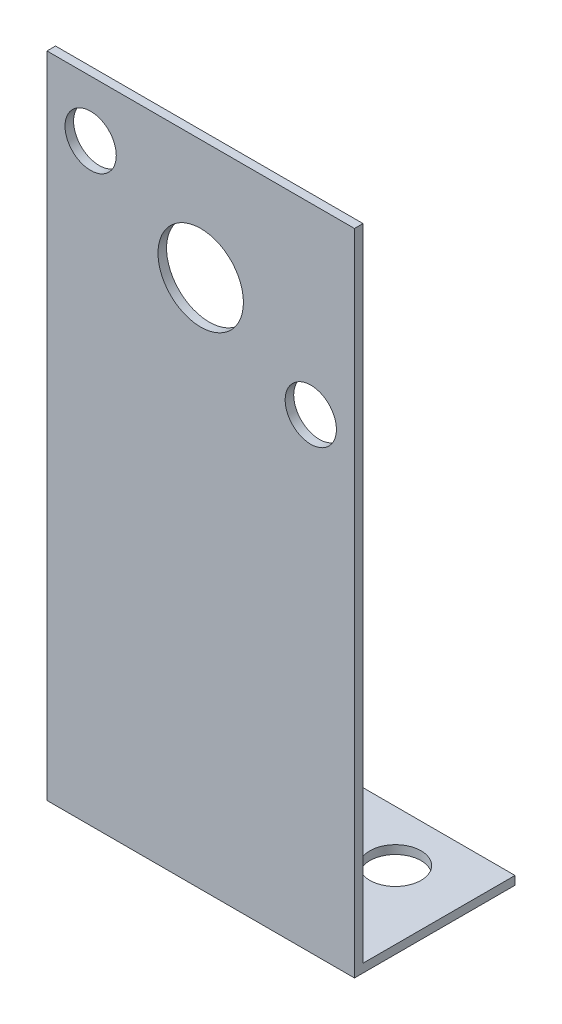
SolidWorks part; units mm, degrees
ref_plane "Front" through (0, 0, 0) normal (0, 0, 1) x (1, 0, 0)
ref_plane "Top" through (0, 0, 0) normal (0, 1, 0) x (1, 0, 0)
ref_plane "Right" through (0, 0, 0) normal (1, 0, 0) x (0, 0, -1)
sketch "Sketch1" plane through (0, 0, 0) normal (0, 0, 1) x (1, 0, 0)
  line L1 (-9, 7) -> (9, 7)
  line L2 (-9, 7) -> (-9, -31)
  line L3 (-9, -31) -> (9, -31)
  line L4 (9, 7) -> (9, -31)
  circle A0 centre (0, 0) radius 2.5
  dimension "D5" = 5
  dimension "D1" = 9
  dimension "D2" = 9
  dimension "D3" = 7
  dimension "D4" = 31
extrude "Extrude1" add sketch "Sketch1" along normal blind 0.5
sketch "Sketch2" plane through (0, 0, 0) normal (0, 0, -1) x (-1, 0, 0)
  line L0 (-9, -31) -> (-9, 7) construction
  line L1 (9, -31) -> (-9, -31)
  line L2 (9, -31) -> (9, -30.5)
  line L3 (9, -30.5) -> (-9, -30.5)
  line L4 (-9, -31) -> (-9, -30.5)
  dimension "D1" = 0.5
extrude "Extrude2" add sketch "Sketch2" along normal blind 8.9
sketch "Sketch3" plane through (0, -30.5, 0) normal (0, 1, 0) x (1, 0, 0)
  line L0 (-9, 8.9) -> (9, 8.9) construction
  line L1 (-9, 8.9) -> (-9, 0) construction
  line L2 (9, 8.9) -> (9, 0) construction
  circle A0 centre (-5, 5.9) radius 1.5
  circle A1 centre (5, 5.9) radius 1.5
  dimension "D4" = 3
  dimension "D5" = 3
  dimension "D1" = 3
  dimension "D2" = 4
  dimension "D3" = 4
extrude "Extrude3" cut sketch "Sketch3" against normal up to surface (0.5 mm away) up to face at (0, -31, -4.2)
sketch "Sketch4" plane through (0, 0, 0) normal (0, 0, -1) x (-1, 0, 0)
  circle A0 centre (-6.4432, -3.72) radius 1.5
  circle A1 centre (6.4432, 3.72) radius 1.5
  dimension "D1" = 3
  dimension "D2" = 3
  dimension "D3" = 7.44
  dimension "D4" = 7.44
  dimension "D5" = 3.72
  dimension "D6" = 3.72
extrude "Extrude4" cut sketch "Sketch4" against normal up to surface (0.5 mm away) up to face at (0, -12, 0.5)
